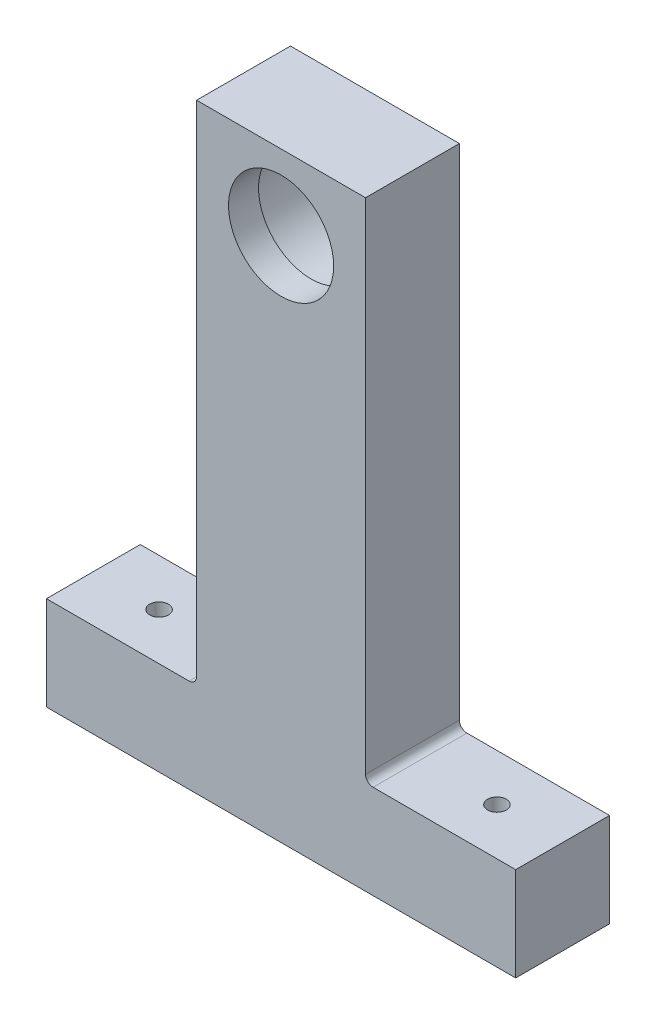
SolidWorks part; units mm, degrees
ref_plane "前视基准面" through (0, 0, 0) normal (0, 0, 1) x (1, 0, 0)
ref_plane "上视基准面" through (0, 0, 0) normal (0, 1, 0) x (1, 0, 0)
ref_plane "右视基准面" through (0, 0, 0) normal (1, 0, 0) x (0, 0, -1)
sketch "草图1" plane through (0, 0, 0) normal (0, 0, 1) x (1, 0, 0)
  line L0 (-22.5, 50) -> (22.5, 50)
  line L2 (-22.5, 50) -> (-22.5, -85)
  line L3 (-22.5, -110) -> (22.5, -110)
  line L4 (22.5, 50) -> (22.5, -85)
  line L5 (0, -110) -> (0, 50) construction
  line L6 (-22.5, 0) -> (22.5, 0) construction
  line L7 (22.5, -85) -> (62.5, -85)
  line L8 (62.5, -85) -> (62.5, -110)
  line L9 (62.5, -110) -> (22.5, -110)
  line L10 (-62.5, -110) -> (-22.5, -110)
  line L11 (-62.5, -85) -> (-62.5, -110)
  line L12 (-22.5, -85) -> (-62.5, -85)
  circle A0 centre (0, 30) radius 16
  point P0 (0, 0)
  dimension "D1" = 32
  dimension "D2" = 45
  dimension "D3" = 30
  dimension "D4" = 140
  dimension "D5" = 20
  dimension "D6" = 25
  dimension "D7" = 45
  dimension "D8" = 40
extrude "凸台-拉伸1" add sketch "草图1" along normal blind 25
fillet "圆角1" radius 2 2 edges at (-22.5, -85, 12.5) (22.5, -85, 12.5)
sketch "草图3" plane through (0, -85, 0) normal (0, 1, 0) x (1, 0, 0)
  line L1 (-24.5, 0) -> (-62.5, 0) construction
  circle A0 centre (-45, -12.5) radius 2.5
  circle A1 centre (45, -12.5) radius 2.5
  dimension "D3" = 5
  dimension "D4" = 12.5
  dimension "D1" = 45
  dimension "D2" = 45
extrude "切除-拉伸1" cut sketch "草图3" against normal blind 30
sketch "草图4" plane through (0, 0, 25) normal (0, 0, 1) x (1, 0, 0)
  circle A0 centre (0, 30) radius 16
  circle A1 centre (0, 30) radius 14
  dimension "D1" = 28
extrude "凸台-拉伸2" add sketch "草图4" against normal blind 8
